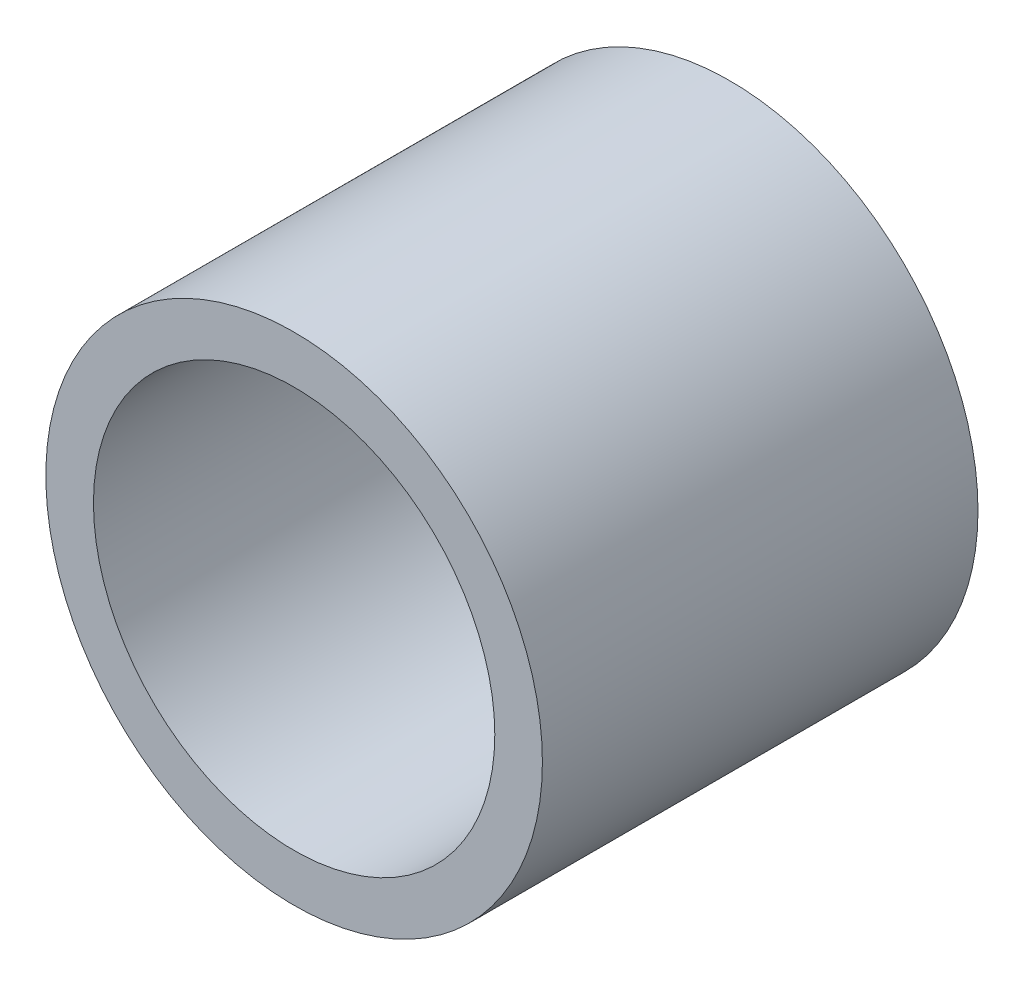
SolidWorks part; units mm, degrees
ref_plane "Front Plane" through (0, 0, 0) normal (0, 0, 1) x (1, 0, 0)
ref_plane "Top Plane" through (0, 0, 0) normal (0, 1, 0) x (1, 0, 0)
ref_plane "Right Plane" through (0, 0, 0) normal (1, 0, 0) x (0, 0, -1)
sketch "Adapter_8OD_6p45ID_profile" plane through (0, 0, 0) normal (0, 0, 1) x (1, 0, 0)
  circle A0 centre (0, 0) radius 3.99
  circle A1 centre (0, 0) radius 3.225
  dimension "D1" = 7.98
  dimension "D2" = 6.45
extrude "Adapter_8OD_6p45ID" add sketch "Adapter_8OD_6p45ID_profile" along normal blind 7
